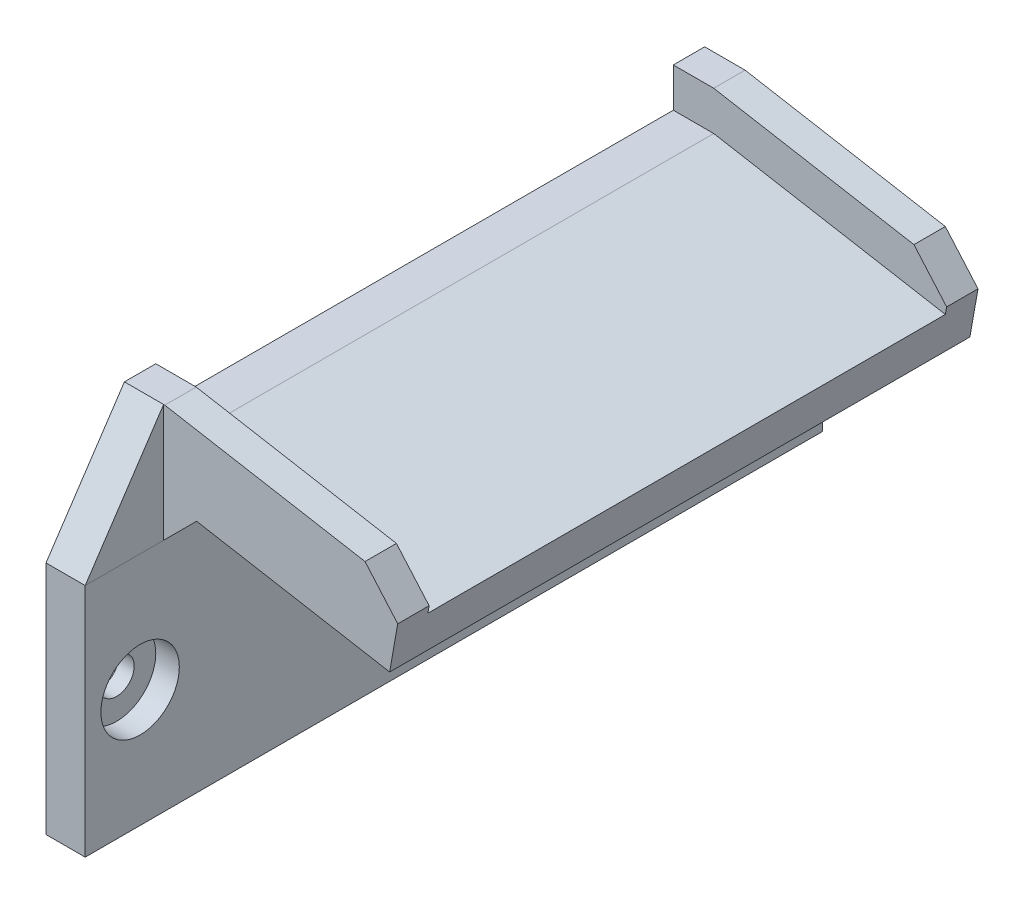
SolidWorks part; units mm, degrees
material "ABS"
ref_plane "Piano frontale" through (0, 0, 0) normal (0, 0, 1) x (1, 0, 0)
ref_plane "Piano superiore" through (0, 0, 0) normal (0, 1, 0) x (1, 0, 0)
ref_plane "Piano destro" through (0, 0, 0) normal (1, 0, 0) x (0, 0, -1)
sketch "Schizzo1" plane through (0, 0, 0) normal (0, 0, 1) x (1, 0, 0)
  line L0 (0, 0) -> (0, 40)
  line L5 (5, 0) -> (0, 0)
  line L6 (0, 40) -> (5.1519, 40)
  line L7 (5.1519, 40) -> (34.6962, 34.7906)
  line L8 (34.6962, 34.7906) -> (33.8279, 29.8665)
  line L9 (33.8279, 29.8665) -> (9.2077, 34.2077)
  line L10 (9.2077, 34.2077) -> (5, 30)
  line L11 (5, 30) -> (5, 0)
  dimension "D1" = 5
  dimension "D2" = 5
  dimension "D3" = 40
  dimension "D4" = 30
  dimension "D5" = 30
  dimension "D6" = 25
  dimension "D7" = 10
  dimension "D8" = 45
extrude "Estrusione-Estrusione1" add sketch "Schizzo1" along normal blind 66
sketch "Schizzo3" plane through (0, 0, 66) normal (0, 0, 1) x (1, 0, 0)
  line L0 (5, 0) -> (5, 30)
  line L1 (5, 30) -> (9.2077, 34.2077)
  line L2 (9.2077, 34.2077) -> (33.8279, 29.8665)
  line L3 (33.8279, 29.8665) -> (35.5512, 39.6398)
  line L4 (5.1519, 45) -> (0, 45)
  line L5 (0, 45) -> (0, 0)
  line L6 (5.1519, 45) -> (35.5512, 39.6398)
  line L7 (34.6962, 34.7906) -> (5.1519, 40) construction
  line L8 (5.1519, 40) -> (0, 40) construction
  line M3 (0, 0) -> (5, 0)
  line M4 (5, 0) -> (5, 30)
  line M5 (5, 30) -> (9.2077, 34.2077)
  line M6 (9.2077, 34.2077) -> (33.8279, 29.8665)
  line M7 (33.8279, 29.8665) -> (34.6962, 34.7906)
  line M8 (34.6962, 34.7906) -> (5.1519, 40)
  line M9 (5.1519, 40) -> (0, 40)
  line M10 (0, 40) -> (0, 0)
  dimension "D1" = 5
extrude "Estrusione-Estrusione2" add sketch "Schizzo3" along normal blind 4 contours M10 M3 M4 M5 M6 M7 M8 M9 | L6 L4 L5 L3 M9 M8
sketch "Schizzo4" plane through (0, 0, 0) normal (0, 0, -1) x (-1, 0, 0)
  line L0 (-5, 0) -> (0, 0)
  line L1 (0, 0) -> (0, 45)
  line L2 (0, 45) -> (-5.1519, 45)
  line L3 (-5.1519, 45) -> (-35.5512, 39.6398)
  line L4 (-35.5512, 39.6398) -> (-33.8279, 29.8665)
  line L5 (-33.8279, 29.8665) -> (-9.2077, 34.2077)
  line L6 (-9.2077, 34.2077) -> (-5, 30)
  line L7 (-5, 30) -> (-5, 0)
extrude "Estrusione-Estrusione3" add sketch "Schizzo4" along normal blind 4
sketch "Schizzo5" plane through (0, 0, -4) normal (0, 0, -1) x (-1, 0, 0)
  line L0 (-5, 0) -> (0, 0)
  line L1 (0, 0) -> (0, 30)
  line L2 (0, 0) -> (0, 45) construction
  line L3 (0, 30) -> (-5, 30)
  line L4 (-5, 30) -> (-5, 0)
extrude "Estrusione-Estrusione4" add sketch "Schizzo5" along normal blind 10
sketch "Schizzo6" plane through (0, 0, 70) normal (0, 0, 1) x (1, 0, 0)
  line L0 (0, 0) -> (0, 30)
  line L1 (0, 30) -> (5, 30)
  line L2 (5, 30) -> (5, 0)
  line L3 (5, 0) -> (0, 0)
extrude "Estrusione-Estrusione5" add sketch "Schizzo6" along normal blind 10
sketch "Schizzo7" plane through (5, 0, 0) normal (1, 0, 0) x (0, 0, -1)
  line L0 (-73, 15) -> (7, 15) construction
  line L2 (-80, 0) -> (14, 0) construction
  line L3 (-80, 0) -> (-80, 30) construction
  line L4 (14, 30) -> (14, 0) construction
  point P0 (-73, 15)
  point P2 (7, 15)
  dimension "D1" = 15
  dimension "D2" = 7
  dimension "D3" = 7
hole_wizard "Foro lamato per Vite M4 a testa cilindrica piana-2" positions "Schizzo7" profile "Schizzo8" counterbore size "M4" standard "ISO"
sketch "Schizzo8" plane through (5, 15, 73) normal (0, 1, 0) x (0, 0, -1)
  line L0 (0, 0) -> (0, 46.3519)
  line L1 (0, 46.3519) -> (2.25, 45)
  line L2 (2.25, 45) -> (2.25, 3)
  line L3 (2.25, 3) -> (5, 3)
  line L4 (5, 3) -> (5, 0)
  line L5 (5, 0) -> (0, 0)
  line L10 (0, 46.3519) -> (-2.25, 45) construction
  line L11 (0, -6.35) -> (0, 107.95) construction
  dimension "Hole Dia." = 4.5
  dimension "Hole Depth" = 45
  dimension "C'Bore Dia." = 10
  dimension "C'Bore Depth" = 3
  dimension "Drill Angle" = 118
sketch "Schizzo9" plane through (0, 0, 0) normal (-1, 0, 0) x (0, 0, 1)
  line L0 (-4, 45) -> (-14, 30)
  line L1 (-14, 0) -> (-14, 30) construction
  line L2 (-14, 30) -> (-4, 30) construction
  line L3 (-14, 30) -> (-4, 30)
  line L4 (-4, 30) -> (-4, 45)
  line L5 (70, 45) -> (70, 30)
  line L6 (70, 30) -> (80, 30)
  line L7 (80, 30) -> (70, 45)
extrude "Estrusione-Estrusione6" add sketch "Schizzo9" against normal blind 5 separate body
chamfer "Smusso2" distance 4 angle 51 1 edges at (35.5512, 39.6398, 68)
chamfer "Smusso3" distance 4 angle 51 1 edges at (35.5512, 39.6398, -2)
